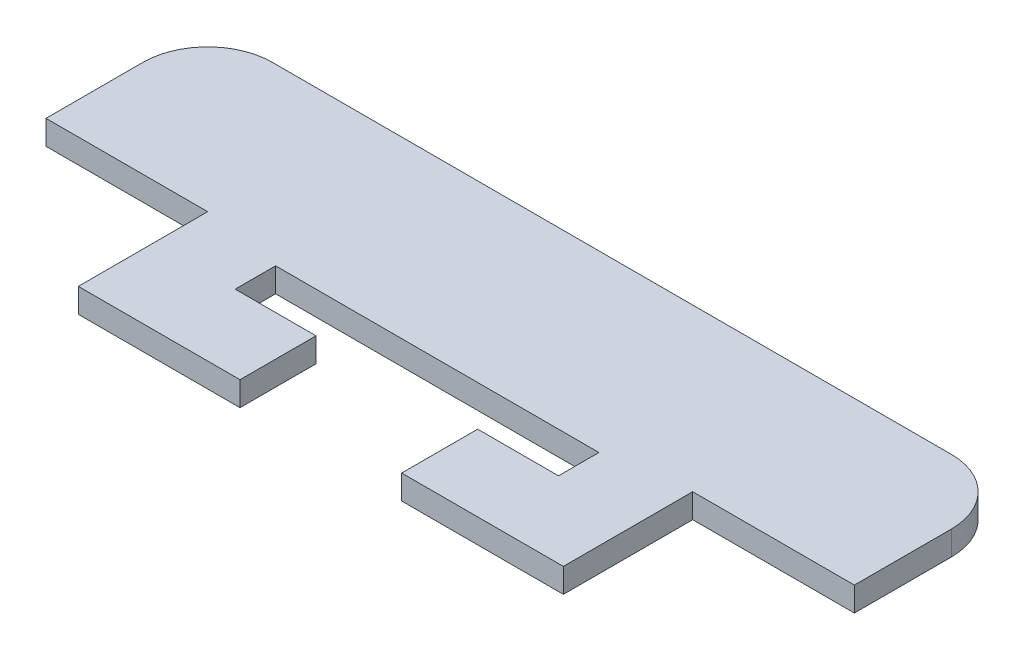
SolidWorks part; units mm, degrees
material "7050-T7651"
ref_plane "Front Plane" through (0, 0, 0) normal (0, 0, 1) x (1, 0, 0)
ref_plane "Top Plane" through (0, 0, 0) normal (0, 1, 0) x (1, 0, 0)
ref_plane "Right Plane" through (0, 0, 0) normal (1, 0, 0) x (0, 0, -1)
sketch "Sketch1" plane through (0, 0, 0) normal (0, 1, 0) x (1, 0, 0)
  line L0 (19.05, 0) -> (31.75, 0)
  line L1 (-31.75, 0) -> (-19.05, 0)
  line L2 (-31.75, 0) -> (-31.75, 12.7)
  line L3 (-31.75, 12.7) -> (31.75, 12.7)
  line L4 (31.75, 0) -> (31.75, 12.7)
  line L6 (-19.05, 0) -> (-19.05, -10.16)
  line L7 (-19.05, -10.16) -> (-12.7, -10.16)
  line L8 (19.05, 0) -> (19.05, -10.16)
  line L9 (12.7, -10.16) -> (19.05, -10.16)
  line L11 (-12.7, -10.16) -> (-12.7, -1.016)
  line L12 (-12.7, -1.016) -> (12.7, -1.016)
  line L13 (12.7, -10.16) -> (12.7, -1.016)
  point P4 (0, 12.7)
  point P11 (0, -1.016)
  dimension "D1" = 63.5
  dimension "D2" = 12.7
  dimension "D3" = 38.1
  dimension "D4" = 10.16
  dimension "D5" = 1.016
  dimension "D6" = 6.35
extrude "Boss-Extrude1" add sketch "Sketch1" along normal blind 1.905
fillet "Fillet1" radius 5.08 2 edges at (31.75, 0.9525, -12.7) (-31.75, 0.9525, -12.7)
sketch "Sketch2" plane through (0, 1.905, 0) normal (0, 1, 0) x (1, 0, 0)
  line L0 (-19.05, 0) -> (-19.05, -10.16) construction
  line L1 (-19.05, -4.191) -> (-6.35, -4.191)
  line L2 (-19.05, -4.191) -> (-19.05, -10.16)
  line L3 (-19.05, -10.16) -> (-6.35, -10.16)
  line L4 (-6.35, -4.191) -> (-6.35, -10.16)
  line L11 (-12.7, -10.16) -> (-12.7, -1.016) construction
  line L12 (-12.7, -1.016) -> (12.7, -1.016) construction
  line L13 (-19.05, -10.16) -> (-12.7, -10.16) construction
  line L14 (0, 14.6701) -> (0, -16.9936) construction
  line L15 (6.35, -4.191) -> (6.35, -10.16)
  line L16 (19.05, -10.16) -> (6.35, -10.16)
  line L17 (19.05, -4.191) -> (19.05, -10.16)
  line L18 (19.05, -4.191) -> (6.35, -4.191)
  dimension "D1" = 6.35
  dimension "D3" = 3.175
extrude "Boss-Extrude2" add sketch "Sketch2" against normal up to surface (1.905 mm away) up to face at (0, 0, -0.0052)
